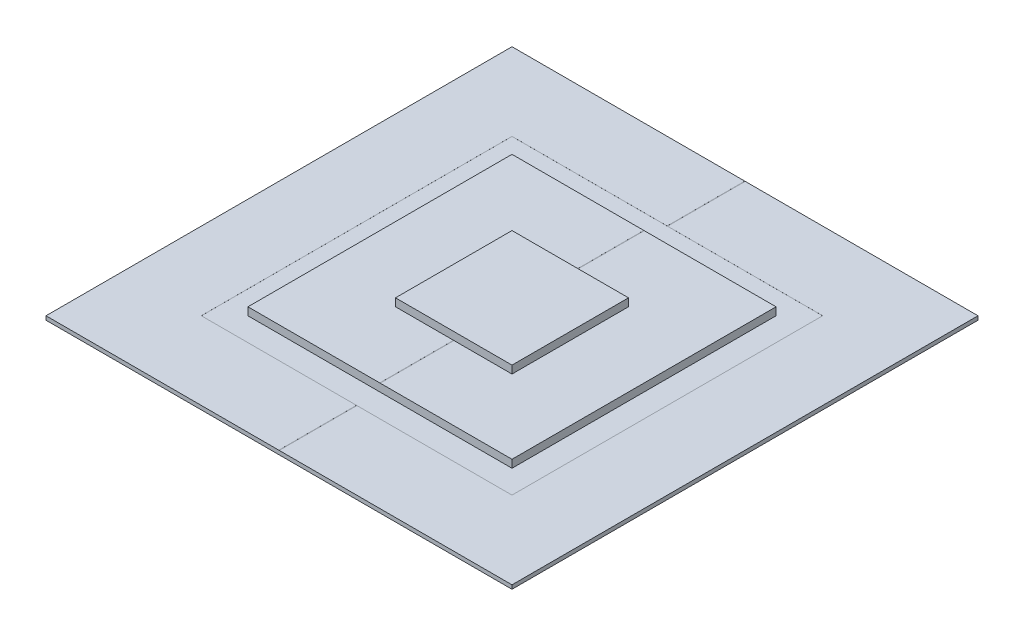
SolidWorks part; units mm, degrees
ref_plane "前视基准面" through (0, 0, 0) normal (0, 0, 1) x (1, 0, 0)
ref_plane "上视基准面" through (0, 0, 0) normal (0, 1, 0) x (1, 0, 0)
ref_plane "右视基准面" through (0, 0, 0) normal (1, 0, 0) x (0, 0, -1)
sketch "Sketch1" plane through (0, 0, 0) normal (0, 1, 0) x (1, 0, 0)
  line L0 (0, 0) -> (0, -12000)
  line L1 (0, -12000) -> (12000, -12000)
  line L2 (12000, -12000) -> (12000, 0)
  line L3 (12000, 0) -> (0, 0)
  line L4 (0, 0) -> (12000, -12000) construction
  line L5 (12000, 0) -> (0, -12000) construction
  line L6 (2600, -2600) -> (2600, -9400)
  line L7 (2600, -9400) -> (9400, -9400)
  line L8 (9400, -9400) -> (9400, -2600)
  line L9 (9400, -2600) -> (2600, -2600)
  line L14 (10000, -2000) -> (2000, -2000)
  line L15 (2000, -2000) -> (2000, -10000)
  line L16 (2000, -10000) -> (10000, -10000)
  line L17 (10000, -10000) -> (10000, -2000)
  dimension "D1" = 12000
  dimension "D2" = 12000
  dimension "D3" = 6800
  dimension "D4" = 600
extrude "Boss-Extrude1" add sketch "Sketch1" along normal blind 100 contours L2 L3 L0 L1 L17 L16 L15 L14 | L9 L6 L7 L8
sketch "Sketch2" plane through (0, 0, 0) normal (0, -1, 0) x (1, 0, 0)
  line L1 (10000, 10000) -> (2000, 10000)
  line L2 (10000, 10000) -> (10000, 2000)
  line L3 (10000, 2000) -> (2000, 2000)
  line L4 (2000, 10000) -> (2000, 2000)
  line L5 (2600, 2600) -> (9400, 2600)
  line L6 (2600, 2600) -> (2600, 9400)
  line L7 (2600, 9400) -> (9400, 9400)
  line L8 (9400, 2600) -> (9400, 9400)
extrude "Boss-Extrude3" add sketch "Sketch2" against normal blind 99
sketch "Sketch3" plane through (0, 100, 0) normal (0, 1, 0) x (1, 0, 0)
  line L0 (6000, 227.8317) -> (6000, -12238.6533) construction
  line L1 (5995, 0) -> (5995, -12000)
  line L2 (6005, 0) -> (6005, -12000)
  line L3 (5995, 0) -> (6005, 0)
  line L4 (12000, 0) -> (0, 0) construction
  line L5 (5995, -12000) -> (6005, -12000)
  line L6 (5995, 227.8317) -> (5995, -12238.6533) construction
  line L7 (6005, 227.8317) -> (6005, -12238.6533) construction
  line L8 (0, -12000) -> (12000, -12000) construction
  dimension "D1" = 5
  dimension "D2" = 5
extrude "Cut-Extrude1" cut sketch "Sketch3" against normal blind 0.5
sketch "Sketch4" plane through (0, 100, 0) normal (0, 1, 0) x (1, 0, 0)
  line L1 (2600, -2600) -> (5995, -2600)
  line L2 (2600, -2600) -> (2600, -9400)
  line L3 (2600, -9400) -> (5995, -9400)
  line L4 (5995, -2600) -> (5995, -9400)
  line L5 (6005, -2600) -> (9400, -2600)
  line L6 (6005, -2600) -> (6005, -9400)
  line L7 (6005, -9400) -> (9400, -9400)
  line L8 (9400, -2600) -> (9400, -9400)
extrude "Boss-Extrude4" add sketch "Sketch4" along normal blind 200
sketch "Sketch5" plane through (0, 99.5, 0) normal (0, 1, 0) x (1, 0, 0)
  line L0 (5995, -2600) -> (6005, -2600)
  line L1 (6005, -2600) -> (6005, -9400)
  line L2 (6005, -9400) -> (5995, -9400)
  line L3 (5995, -9400) -> (5995, -2600)
extrude "Boss-Extrude5" add sketch "Sketch5" along normal blind 200
sketch "Sketch6" plane through (0, 300, 0) normal (0, 1, 0) x (1, 0, 0)
  line L0 (2600, -2600) -> (9400, -9400) construction
  line L1 (9400, -2600) -> (2600, -9400) construction
  line L2 (4500, -4500) -> (4500, -7500)
  line L3 (4500, -7500) -> (7500, -7500)
  line L4 (7500, -7500) -> (7500, -4500)
  line L5 (7500, -4500) -> (4500, -4500)
  dimension "D1" = 3000
extrude "Boss-Extrude6" add sketch "Sketch6" along normal blind 200
